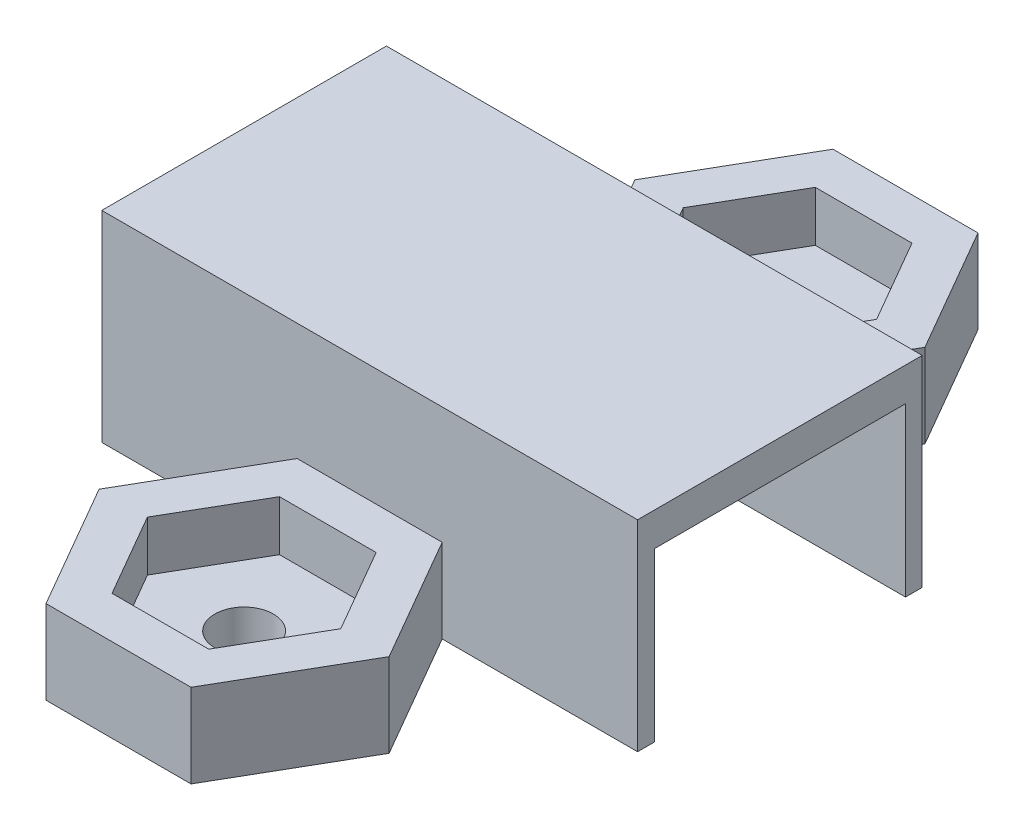
SolidWorks part; units mm, degrees
ref_plane "Front Plane" through (0, 0, 0) normal (0, 0, 1) x (1, 0, 0)
ref_plane "Top Plane" through (0, 0, 0) normal (0, 1, 0) x (1, 0, 0)
ref_plane "Right Plane" through (0, 0, 0) normal (1, 0, 0) x (0, 0, -1)
sketch "Sketch1" plane through (0, 0, 0) normal (0, 1, 0) x (1, 0, 0)
  line L1 (-16, 8.5) -> (16, 8.5)
  line L2 (-16, 8.5) -> (-16, -8.5)
  line L3 (-16, -8.5) -> (16, -8.5)
  line L4 (16, 8.5) -> (16, -8.5)
  line L5 (0, -8.5) -> (0, 8.5) construction
  line L6 (-16, 0) -> (16, 0) construction
  point P4 (0, 0)
  point P116 (0, 0)
  dimension "D1" = 32
  dimension "D2" = 17
extrude "Boss-Extrude1" add sketch "Sketch1" along normal blind 12
sketch "Sketch2" plane through (-16, 0, 0) normal (-1, 0, 0) x (0, 0, 1)
  line L0 (-8.5, 0) -> (8.5, 0) construction
  line L1 (-7.5, 10) -> (7.5, 10)
  line L2 (-7.5, 10) -> (-7.5, 0)
  line L3 (-7.5, 0) -> (7.5, 0)
  line L4 (7.5, 10) -> (7.5, 0)
  line L5 (0, 0) -> (0, 10) construction
  line L6 (-7.5, 5) -> (7.5, 5) construction
  point P6 (0, 0)
  point P10 (0, 0)
  point P240 (0, 5)
  dimension "D1" = 15
  dimension "D2" = 10
extrude "Cut-Extrude1" cut sketch "Sketch2" against normal blind 58
sketch "Sketch3" plane through (0, 0, 0) normal (0, -1, 0) x (1, 0, 0)
  line L0 (16, -8.5) -> (-16, -8.5) construction
  line L1 (4.3301, -8.5) -> (-4.3301, -8.5)
  line L2 (-4.3301, -8.5) -> (-8.6603, -16)
  line L3 (-8.6603, -16) -> (-4.3301, -23.5)
  line L4 (-4.3301, -23.5) -> (4.3301, -23.5)
  line L5 (4.3301, -23.5) -> (8.6603, -16)
  line L6 (8.6603, -16) -> (4.3301, -8.5)
  line L7 (-16, 0) -> (-9.6017, 0) construction
  line L8 (-16, 7.5) -> (-16, -7.5) construction
  line L9 (8.6603, 16) -> (4.3301, 8.5)
  line L10 (4.3301, 23.5) -> (8.6603, 16)
  line L11 (-4.3301, 23.5) -> (4.3301, 23.5)
  line L12 (-8.6603, 16) -> (-4.3301, 23.5)
  line L13 (-4.3301, 8.5) -> (-8.6603, 16)
  line L14 (4.3301, 8.5) -> (-4.3301, 8.5)
  circle A0 centre (0, -16) radius 7.5 construction
  point P10 (0, -8.5)
  point P11 (0, -8.5)
  dimension "D1" = 15
extrude "Boss-Extrude2" add sketch "Sketch3" against normal blind 5
sketch "Sketch4" plane through (0, 5, 0) normal (0, 1, 0) x (1, 0, 0)
  line L0 (8.6603, 16) -> (-8.6603, 16) construction
  line L1 (8.6603, 16) -> (4.3301, 8.5) construction
  line L2 (2.8868, 11) -> (5.7735, 16)
  line L3 (5.7735, 16) -> (2.8868, 21)
  line L4 (2.8868, 21) -> (-2.8868, 21)
  line L5 (-2.8868, 21) -> (-5.7735, 16)
  line L6 (-5.7735, 16) -> (-2.8868, 11)
  line L7 (-2.8868, 11) -> (2.8868, 11)
  line L8 (8.6603, -16) -> (-8.6603, -16) construction
  line L9 (8.6603, -16) -> (4.3301, -23.5) construction
  line L10 (2.8868, -21) -> (5.7735, -16)
  line L11 (5.7735, -16) -> (2.8868, -11)
  line L12 (2.8868, -11) -> (-2.8868, -11)
  line L13 (-2.8868, -11) -> (-5.7735, -16)
  line L14 (-5.7735, -16) -> (-2.8868, -21)
  line L15 (-2.8868, -21) -> (2.8868, -21)
  circle A0 centre (0, 16) radius 5 construction
  circle A1 centre (0, -16) radius 5 construction
  dimension "D1" = 10
  dimension "D2" = 10
extrude "Cut-Extrude2" cut sketch "Sketch4" against normal blind 3
sketch "Sketch5" plane through (0, 2, 0) normal (0, 1, 0) x (1, 0, 0)
  line L0 (5.7735, 16) -> (-5.7735, 16) construction
  line L1 (5.7735, -16) -> (-5.7735, -16) construction
  circle A0 centre (0, 16) radius 1.75
  circle A1 centre (0, -16) radius 1.75
  dimension "D1" = 3.5
  dimension "D2" = 3.5
extrude "Cut-Extrude3" cut sketch "Sketch5" against normal blind 4
